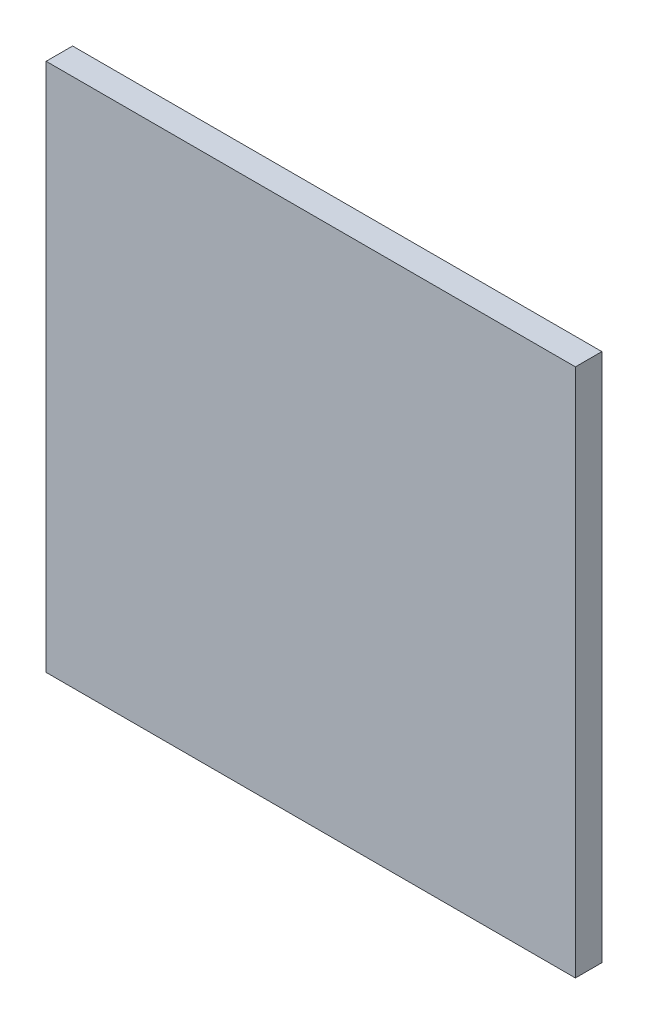
SolidWorks part; units mm, degrees
ref_plane "Alzado" through (0, 0, 0) normal (0, 0, 1) x (1, 0, 0)
ref_plane "Planta" through (0, 0, 0) normal (0, 1, 0) x (1, 0, 0)
ref_plane "Vista lateral" through (0, 0, 0) normal (1, 0, 0) x (0, 0, -1)
sketch "Croquis1" plane through (0, 0, 0) normal (0, 0, 1) x (1, 0, 0)
  line L1 (0, 0) -> (-100, 0)
  line L2 (0, 0) -> (0, -100)
  line L3 (0, -100) -> (-100, -100)
  line L4 (-100, 0) -> (-100, -100)
  dimension "D1" = 100
  dimension "D2" = 100
extrude "Saliente-Extruir1" add sketch "Croquis1" along normal blind 5
